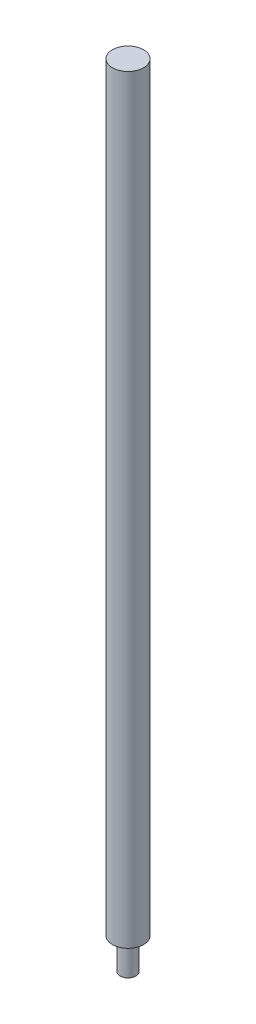
SolidWorks part; units mm, degrees
ref_plane "Front Plane" through (0, 0, 0) normal (0, 0, 1) x (1, 0, 0)
ref_plane "Top Plane" through (0, 0, 0) normal (0, 1, 0) x (1, 0, 0)
ref_plane "Right Plane" through (0, 0, 0) normal (1, 0, 0) x (0, 0, -1)
sketch "Sketch1" plane through (0, 0, 0) normal (0, 1, 0) x (1, 0, 0)
  circle A0 centre (0, 0) radius 4.7625
  dimension "D1" = 9.525
extrude "Boss-Extrude1" add sketch "Sketch1" along normal blind 241.3
sketch "Sketch2" plane through (0, 0, 0) normal (0, -1, 0) x (1, 0, 0)
  circle A0 centre (0, 0) radius 4.7625
  circle A1 centre (0, 0) radius 2.3813
  circle A2 centre (0, 0) radius 4.7625 construction
  dimension "D1" = 4.7625
extrude "Cut-Extrude1" cut sketch "Sketch2" against normal blind 9.525
